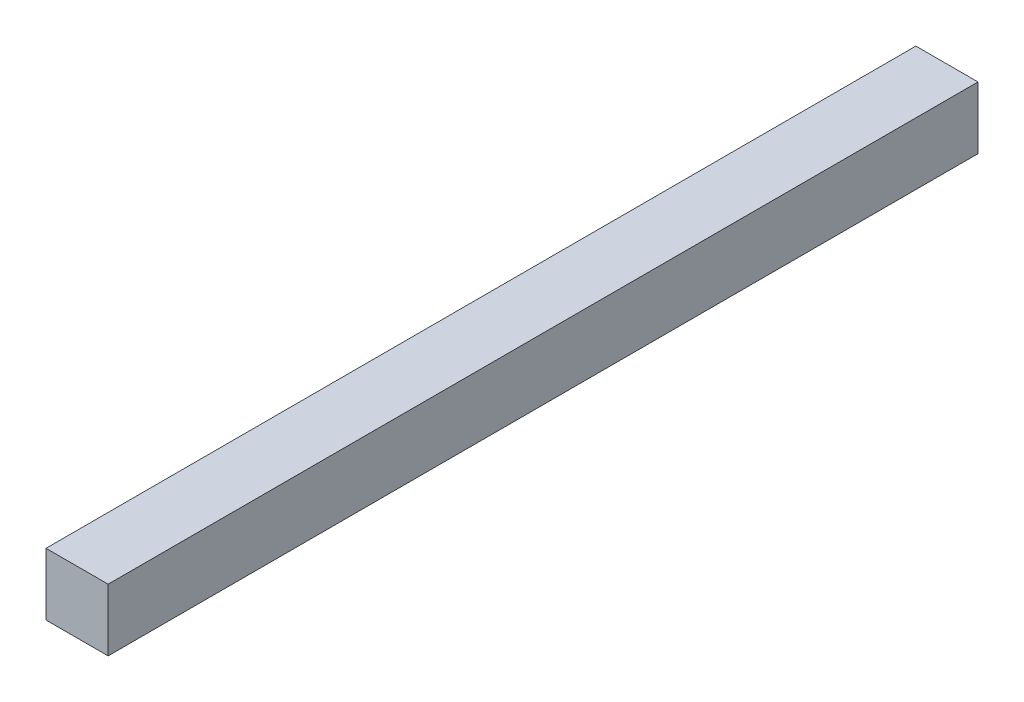
SolidWorks part; units mm, degrees
ref_plane "Přední rovina" through (0, 0, 0) normal (0, 0, 1) x (1, 0, 0)
ref_plane "Horní rovina" through (0, 0, 0) normal (0, 1, 0) x (1, 0, 0)
ref_plane "Pravá rovina" through (0, 0, 0) normal (1, 0, 0) x (0, 0, -1)
sketch "Skica1" plane through (0, 0, 0) normal (0, 0, 1) x (1, 0, 0)
  line L1 (0, 0) -> (0.8, 0)
  line L2 (0, 0) -> (0, 0.8)
  line L3 (0, 0.8) -> (0.8, 0.8)
  line L4 (0.8, 0) -> (0.8, 0.8)
  dimension "D1" = 0.8
extrude "Přidat vysunutím1" add sketch "Skica1" along normal blind 11.2
